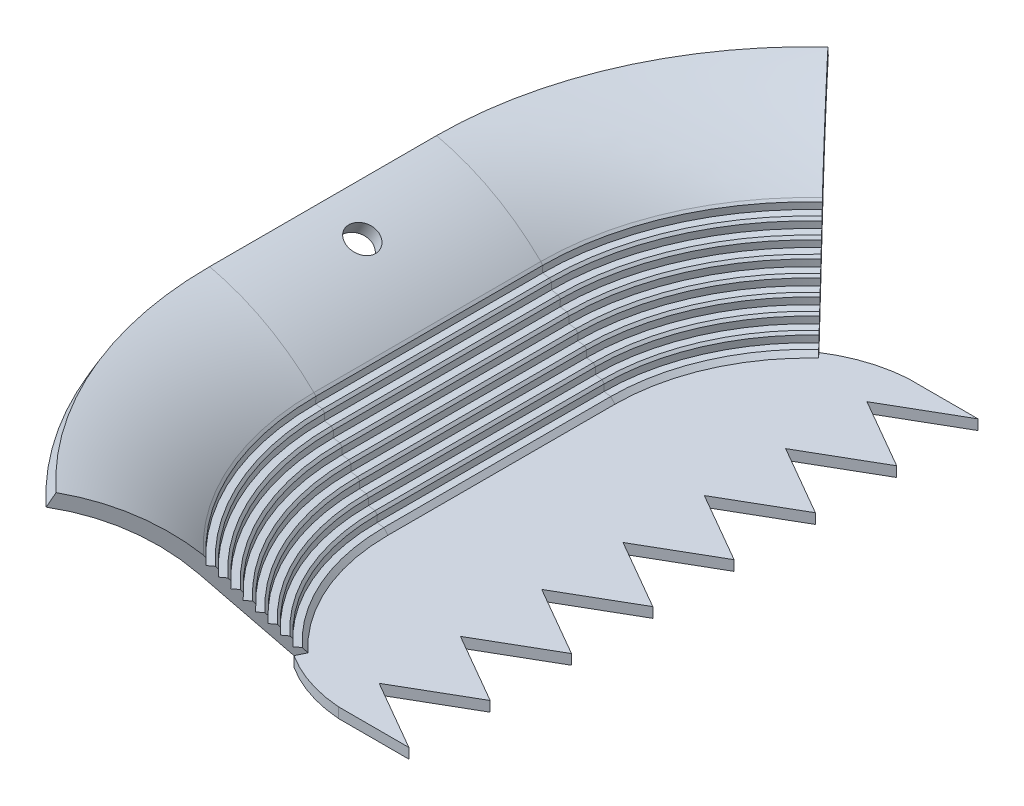
SolidWorks part; units mm, degrees
ref_plane "Front Plane" through (0, 0, 0) normal (0, 0, 1) x (1, 0, 0)
ref_plane "Top Plane" through (0, 0, 0) normal (0, 1, 0) x (1, 0, 0)
ref_plane "Right Plane" through (0, 0, 0) normal (1, 0, 0) x (0, 0, -1)
sketch "Sketch1" plane through (0, 0, 0) normal (0, 0, 1) x (1, 0, 0)
  line L0 (0, 0) -> (-56.2176, 0) construction
  line L8 (-5.6359, 7.157) -> (1, 0)
  line L9 (-16.2506, 13.11) -> (-15.5645, 14.332)
  line L11 (-5.3062, 8.737) -> (1.978, 0.2084)
  line L12 (1.978, 0.2084) -> (1, 0)
  line L13 (-16.2506, 13.11) -> (2.1364, 13.11) construction
  arc A1 (-16.2506, 13.11) -> (-5.6359, 7.157) centre (-20.2626, -6.4835) cw
  arc A2 (-15.5645, 14.332) -> (-5.3062, 8.737) centre (-20.2626, -6.4835) cw
  dimension "D2" = 1
  dimension "D4" = 20
  dimension "D5" = 60.69
  dimension "D7" = 21.339
  dimension "D3" = 192.03
  dimension "D6" = 47.163
  dimension "D8" = 1
  dimension "D9" = 9.76
  dimension "D10" = 13.11
  dimension "D11" = 12.17
  dimension "D12" = 1.58
extrude "Boss-Extrude1" add sketch "Sketch1" along normal mid plane 13.33
sketch "Sketch2" plane through (0, 0, 6.665) normal (0, 0, 1) x (1, 0, 0)
  line L0 (-5.1114, 8.5088) -> (-5.1312, 7.8391)
  line L1 (-5.1312, 7.8391) -> (-4.4666, 7.7539)
  line L3 (1.978, 0.2084) -> (-5.3062, 8.737) construction
  line L4 (-4.789, 8.1314) -> (-5.5469, 7.4841) construction
  dimension "D1" = 0.67
  dimension "D2" = 0.45
  dimension "D3" = 0.3
extrude "Cut-Extrude2" cut sketch "Sketch2" against normal through all and the other way through all
pattern_linear "LPattern1" count 8 spacing 1.33 along (0.6495, -0.7604, 0) of "Cut-Extrude2"
sketch "Sketch3" plane through (0, 0, 6.665) normal (0, 0, 1) x (1, 0, 0)
  line L48 (-5.1114, 8.5088) -> (-5.3062, 8.737) construction
  line L49 (-5.1114, 8.5088) -> (-5.1312, 7.8391) construction
  line L50 (-5.1312, 7.8391) -> (-4.4666, 7.7539) construction
  line L51 (-4.2476, 7.4975) -> (-4.4666, 7.7539) construction
  line L52 (-4.2476, 7.4975) -> (-4.2674, 6.8278) construction
  line L53 (-4.2674, 6.8278) -> (-3.6028, 6.7426) construction
  line L54 (-3.3838, 6.4862) -> (-3.6028, 6.7426) construction
  line L55 (-3.3838, 6.4862) -> (-3.4036, 5.8165) construction
  line L56 (-3.4036, 5.8165) -> (-2.739, 5.7313) construction
  line L57 (-2.52, 5.4749) -> (-2.739, 5.7313) construction
  line L58 (-2.52, 5.4749) -> (-2.5398, 4.8051) construction
  line L59 (-2.5398, 4.8051) -> (-1.8753, 4.7199) construction
  line L60 (-1.6563, 4.4635) -> (-1.8753, 4.7199) construction
  line L61 (-1.6563, 4.4635) -> (-1.676, 3.7938) construction
  line L62 (-1.676, 3.7938) -> (-1.0115, 3.7086) construction
  line L63 (-0.7925, 3.4522) -> (-1.0115, 3.7086) construction
  line L64 (-0.7925, 3.4522) -> (-0.8123, 2.7825) construction
  line L65 (-0.8123, 2.7825) -> (-0.1477, 2.6973) construction
  line L66 (0.0713, 2.4409) -> (-0.1477, 2.6973) construction
  line L67 (0.0713, 2.4409) -> (0.0515, 1.7712) construction
  line L68 (0.0515, 1.7712) -> (0.7161, 1.686) construction
  line L69 (0.9351, 1.4295) -> (0.7161, 1.686) construction
  line L70 (0.9351, 1.4295) -> (0.9153, 0.7598) construction
  line L71 (0.9153, 0.7598) -> (1.5798, 0.6746) construction
  line L72 (1.978, 0.2084) -> (1.5798, 0.6746) construction
  line L73 (1, 0) -> (1.978, 0.2084) construction
  line L74 (-5.6359, 7.157) -> (1, 0) construction
  line L75 (-15.5645, 14.332) -> (-16.2506, 13.11) construction
  line L76 (-5.1114, 8.5088) -> (-5.3062, 8.737)
  line L77 (-5.1114, 8.5088) -> (-5.1312, 7.8391)
  line L78 (-5.1312, 7.8391) -> (-4.4666, 7.7539)
  line L79 (-4.2476, 7.4975) -> (-4.4666, 7.7539)
  line L80 (-4.2476, 7.4975) -> (-4.2674, 6.8278)
  line L81 (-4.2674, 6.8278) -> (-3.6028, 6.7426)
  line L82 (-3.3838, 6.4862) -> (-3.6028, 6.7426)
  line L83 (-3.3838, 6.4862) -> (-3.4036, 5.8165)
  line L84 (-3.4036, 5.8165) -> (-2.739, 5.7313)
  line L85 (-2.52, 5.4749) -> (-2.739, 5.7313)
  line L86 (-2.52, 5.4749) -> (-2.5398, 4.8051)
  line L87 (-2.5398, 4.8051) -> (-1.8753, 4.7199)
  line L88 (-1.6563, 4.4635) -> (-1.8753, 4.7199)
  line L89 (-1.6563, 4.4635) -> (-1.676, 3.7938)
  line L90 (-1.676, 3.7938) -> (-1.0115, 3.7086)
  line L91 (-0.7925, 3.4522) -> (-1.0115, 3.7086)
  line L92 (-0.7925, 3.4522) -> (-0.8123, 2.7825)
  line L93 (-0.8123, 2.7825) -> (-0.1477, 2.6973)
  line L94 (0.0713, 2.4409) -> (-0.1477, 2.6973)
  line L95 (0.0713, 2.4409) -> (0.0515, 1.7712)
  line L96 (0.0515, 1.7712) -> (0.7161, 1.686)
  line L97 (0.9351, 1.4295) -> (0.7161, 1.686)
  line L98 (0.9351, 1.4295) -> (0.9153, 0.7598)
  line L99 (0.9153, 0.7598) -> (1.5798, 0.6746)
  line L100 (1.978, 0.2084) -> (1.5798, 0.6746)
  line L101 (1, 0) -> (1.978, 0.2084)
  line L102 (-5.6359, 7.157) -> (1, 0)
  line L103 (-15.5645, 14.332) -> (-16.2506, 13.11)
  arc A4 (-5.6359, 7.157) -> (-16.2506, 13.11) centre (-20.2626, -6.4835) ccw construction
  arc A5 (-5.3062, 8.737) -> (-15.5645, 14.332) centre (-20.2626, -6.4835) ccw construction
  arc A6 (-5.6359, 7.157) -> (-16.2506, 13.11) centre (-20.2626, -6.4835) ccw
  arc A7 (-5.3062, 8.737) -> (-15.5645, 14.332) centre (-20.2626, -6.4835) ccw
sketch "Sketch5" plane through (0, 0, 0) normal (0, 1, 0) x (1, 0, 0)
  line L0 (1, -6.665) -> (1, -11.165)
  arc A0 (1, -11.165) -> (7.4, -25.8292) centre (21, -11.165) ccw
  dimension "D3" = 20
  dimension "D1" = 4.5
  dimension "D2" = 16
sweep "Sweep1" add profiles "Sketch3" path "Sketch5"
mirror "Mirror1" about plane through (0, 0, 0) normal (0, 0, 1) of "Sweep1"
sketch "Sketch9" plane through (0, 0, 0) normal (0, 1, 0) x (1, 0, 0)
  line L0 (13.9496, -24) -> (20.8778, -20)
  line L1 (20.8778, -20) -> (13.9496, -16)
  line L2 (1, -11.165) -> (1, 11.165) construction
  line L5 (1, -11.165) -> (1, 11.165)
  line L20 (13.9496, -16) -> (20.8778, -12)
  line L21 (20.8778, -12) -> (13.9496, -8)
  line L22 (13.9496, -8) -> (20.8778, -4)
  line L23 (20.8778, -4) -> (13.9496, 0)
  line L24 (13.9496, 0) -> (20.8778, 4)
  line L25 (20.8778, 4) -> (13.9496, 8)
  line L26 (13.9496, 8) -> (20.8778, 12)
  line L27 (20.8778, 12) -> (13.9496, 16)
  line L28 (13.9496, 16) -> (20.8778, 20)
  line L29 (20.8778, 20) -> (13.9496, 24)
  line L30 (13.9496, 24) -> (20.8778, 28)
  line L31 (20.8778, 28) -> (13.9496, 28)
  line L32 (13.9496, -24) -> (20.8778, -28)
  line L33 (20.8778, -28) -> (13.9496, -28)
  arc A0 (7.4, 25.8292) -> (1, 11.165) centre (21, 11.165) ccw construction
  arc A1 (1, -11.165) -> (7.4, -25.8292) centre (21, -11.165) ccw construction
  arc A2 (7.4, 25.8292) -> (1, 11.165) centre (21, 11.165) ccw
  arc A3 (1, -11.165) -> (7.4, -25.8292) centre (21, -11.165) ccw
  arc A4 (7.4, 25.8292) -> (13.9496, 28) centre (14.9434, 14.0353) cw
  arc A5 (7.4, -25.8292) -> (13.9496, -28) centre (14.9434, -14.0353) ccw
  dimension "D5" = 14
  dimension "D1" = 28
  dimension "D2" = 56
  dimension "D3" = 28
  dimension "D4" = 6.9
  dimension "D6" = 8
  dimension "D7" = 8
  dimension "D8" = 4
  dimension "D9" = 8
  dimension "D10" = 8
  dimension "D11" = 8
  dimension "D12" = 8
  dimension "D13" = 8
  dimension "D14" = 4
extrude "Boss-Extrude2" add sketch "Sketch9" against normal blind 1 separate body
ref_plane "Plane1" through (-18.0476, -32.1895, 0) normal (-0.489, -0.8723, 0) x (-0.8723, 0.489, 0)
sketch "Sketch10" plane through (-18.0476, -32.1895, 0) normal (-0.489, -0.8723, 0) x (-0.8723, 0.489, 0)
  line L0 (20.5853, -11.165) -> (20.5853, 11.165) construction
  line L1 (8.9012, -11.165) -> (20.5853, -11.165) construction
  circle A0 centre (24.2853, -22.335) radius 1.425
  dimension "D2" = 2.85
  dimension "D1" = 3.7
  dimension "D3" = 11.17
extrude "Cut-Extrude3" [suppressed] cut sketch "Sketch10" against normal blind 10
extrude "Cut-Extrude4" cut sketch "Sketch11" against normal through all
sketch "Sketch11" plane through (-18.0476, -32.1895, 0) normal (-0.489, -0.8723, 0) x (-0.8723, 0.489, 0)
  circle A2 centre (16.5861, 0) radius 1.425
